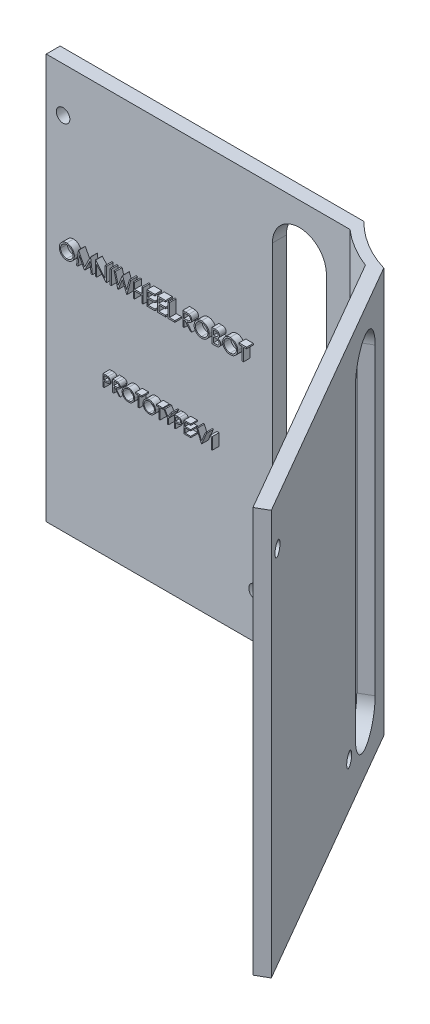
SolidWorks part; units mm, degrees
ref_plane "Plan de face" through (0, 0, 0) normal (0, 0, 1) x (1, 0, 0)
ref_plane "Plan de dessus" through (0, 0, 0) normal (0, 1, 0) x (1, 0, 0)
ref_plane "Plan de droite" through (0, 0, 0) normal (1, 0, 0) x (0, 0, -1)
sketch "Esquisse3" plane through (0, 0, 0) normal (0, 1, 0) x (1, 0, 0)
  line L0 (-150.1573, 0) -> (189.6273, 0) construction
  line L1 (-83.8395, -145.9242) -> (87.7229, 151.2306) construction
  line L2 (-78.0725, 135.2255) -> (117.7517, -203.9519) construction
  line L3 (-125, 131.2995) -> (-125, -153.5705) construction
  line L4 (-25, -24.4949) -> (-115, -24.4949)
  line L6 (-21.2883, 25.5051) -> (-23.9685, 25.5051)
  line L7 (-115, -24.4949) -> (-115, 25.5051)
  line L8 (-25, -24.4949) -> (-115, 25.5051) construction
  line L9 (-21.2883, 25.5051) -> (-115, -24.4949) construction
  line L10 (-23.9685, 25.5051) -> (-115, 25.5051)
  line L11 (34.0723, 8.0048) -> (79.5881, 86.8404)
  line L12 (36.2868, 111.8404) -> (79.5881, 86.8404)
  line L13 (-8.7132, 33.8981) -> (36.2868, 111.8404)
  line L14 (-10.1038, -33.5099) -> (35.4119, -112.3455)
  line L15 (78.7132, -87.3455) -> (35.4119, -112.3455)
  line L16 (33.7132, -9.4032) -> (78.7132, -87.3455)
  line L17 (-23.9685, 25.5051) -> (-25, -24.4949)
  line L18 (-8.7132, 33.8981) -> (34.0723, 8.0048)
  line L19 (-10.1038, -33.5099) -> (33.7132, -9.4032)
  line L20 (-25, -28.6182) -> (-115, -28.6182)
  line L21 (-115, -28.6182) -> (-115, -24.4949)
  line L22 (-13.5526, -35.5011) -> (31.9631, -114.3367)
  line L23 (31.9631, -114.3367) -> (35.4119, -112.3455)
  circle A0 centre (0, 0) radius 125
  circle A1 centre (0, 0) radius 35
  circle A2 centre (0, 0) radius 125
  circle A3 centre (0, 0) radius 125
  circle A4 centre (0, 0) radius 38
  point P9 (-69.0908, 0)
  point P32 (0, 0)
  dimension "D1" = 250
  dimension "D4" = 70
  dimension "D2" = 120
  dimension "D3" = 120
  dimension "D5" = 10
  dimension "D6" = 50
  dimension "D7" = 90
  dimension "D9" = 3
  dimension "D8" = 3
extrude "Boss.-Extru.1" add sketch "Esquisse3" along normal blind 120 contours A4 L4 L21 L20 | L4 A4 L14 A1 | A4 L22 L23 L14
sketch "Esquisse4" plane through (0, 0, 28.6182) normal (0, 0, 1) x (1, 0, 0)
  line L0 (-40, 120) -> (-40, 0) construction
  line L1 (-25, 120) -> (-115, 120) construction
  line L2 (-25, 0) -> (-115, 0) construction
  line L3 (-48, 105) -> (-48, 15)
  line L4 (-25, 120) -> (-25, 0) construction
  line L5 (-115, 60) -> (-20.315, 60) construction
  line L6 (-115, 120) -> (-115, 0) construction
  line L7 (-32, 105) -> (-32, 15)
  arc A0 (-48, 15) -> (-32, 15) centre (-40, 15) ccw
  arc A1 (-48, 105) -> (-32, 105) centre (-40, 105) cw
  dimension "D1" = 8
  dimension "D2" = 15
  dimension "D3" = 45
  dimension "D4" = 45
extrude "Enlèv. mat.-Extru.1" cut sketch "Esquisse4" against normal through all
sketch "Esquisse5" plane through (-25.5369, 0, 14.7437) normal (-0.866, 0, 0.5) x (0.5, 0, 0.866)
  line L0 (38.9685, 120) -> (38.9685, 0) construction
  line L1 (23.9685, 120) -> (115, 120) construction
  line L2 (46.9685, 105) -> (46.9685, 15)
  line L3 (38.9685, 60) -> (127.8483, 60) construction
  line L4 (115, 120) -> (115, 0) construction
  line L5 (23.9685, 120) -> (23.9685, 0) construction
  line L6 (30.9685, 105) -> (30.9685, 15)
  arc A0 (46.9685, 15) -> (30.9685, 15) centre (38.9685, 15) cw
  arc A1 (46.9685, 105) -> (30.9685, 105) centre (38.9685, 105) ccw
  point P14 (115, 60)
  dimension "D1" = 8
  dimension "D2" = 45
  dimension "D3" = 45
  dimension "D4" = 15
extrude "Enlèv. mat.-Extru.2" cut sketch "Esquisse5" against normal through all
sketch "Esquisse6" plane through (0, 0, 28.6182) normal (0, 0, 1) x (1, 0, 0)
  circle A0 centre (-110, 106.75) radius 2 construction
  circle A1 centre (-110, 106.75) radius 2
sketch "Esquisse7" plane through (-25.5369, 0, 14.7437) normal (-0.866, 0, 0.5) x (0.5, 0, 0.866)
  circle A0 centre (110, 106.75) radius 2 construction
  circle A1 centre (110, 106.75) radius 2
extrude "Enlèv. mat.-Extru.3" cut sketch "Esquisse6" against normal through all
extrude "Enlèv. mat.-Extru.4" cut sketch "Esquisse7" against normal through all
sketch "Esquisse8" plane through (0, 0, 28.6182) normal (0, 0, 1) x (1, 0, 0)
  line L0 (-115, 72.2203) -> (-48, 72.2203) construction
  line L1 (-107.7615, 44.975) -> (-51.4576, 44.975) construction
  line L2 (-115, 120) -> (-115, 0) construction
  line L3 (-48, 105) -> (-48, 15) construction
  text T0 "OMNIWHEEL ROBOT" font "Century Gothic" height in points 16
  text T1 "PROTOTYPE V1" font "Century Gothic" height 3.5
extrude "Boss.-Extru.2" add sketch "Esquisse8" along normal blind 2
sketch "Esquisse9" plane through (0, 0, 28.6182) normal (0, 0, 1) x (1, 0, 0)
  circle A0 centre (-53, 13) radius 2 construction
  circle A1 centre (-53, 13) radius 2
sketch "Esquisse10" plane through (-25.5369, 0, 14.7437) normal (-0.866, 0, 0.5) x (0.5, 0, 0.866)
  circle A0 centre (51.9685, 13) radius 2 construction
  circle A1 centre (51.9685, 13) radius 2
extrude "Enlèv. mat.-Extru.5" cut sketch "Esquisse9" against normal through all
extrude "Enlèv. mat.-Extru.6" cut sketch "Esquisse10" against normal through all
